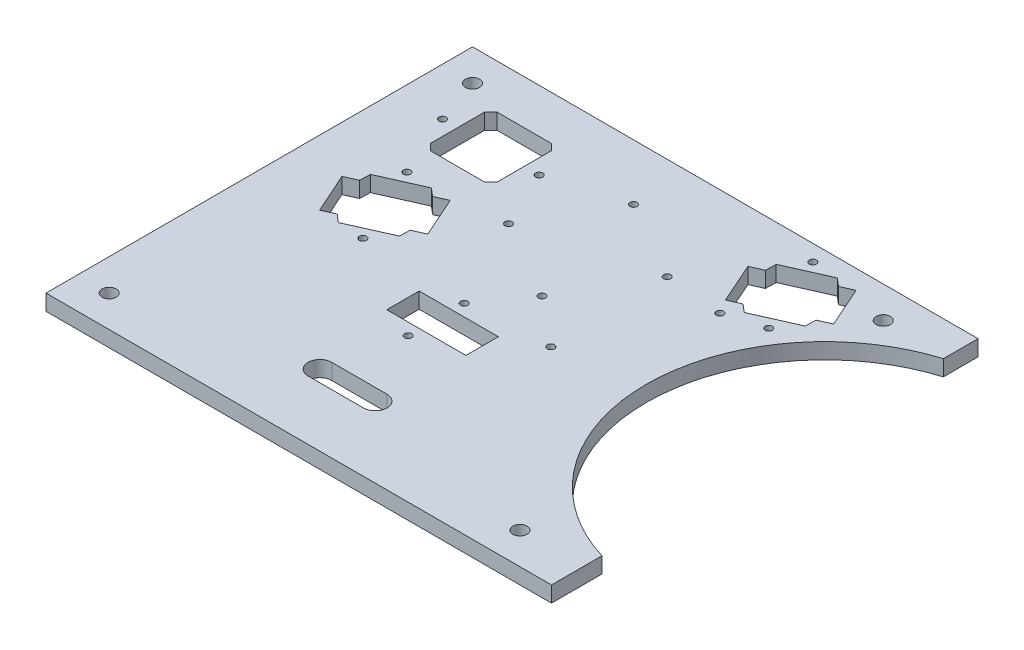
SolidWorks part; units mm, degrees
material "Multistrato di pioppo"
ref_plane "Piano frontale" through (0, 0, 0) normal (0, 0, 1) x (1, 0, 0)
ref_plane "Piano superiore" through (0, 0, 0) normal (0, 1, 0) x (1, 0, 0)
ref_plane "Piano destro" through (0, 0, 0) normal (1, 0, 0) x (0, 0, -1)
sketch "Schizzo1" plane through (0, 0, 0) normal (0, 1, 0) x (1, 0, 0)
  line L1 (-320, 270) -> (0, 270)
  line L2 (-320, 270) -> (-320, 0)
  line L3 (-320, 0) -> (0, 0)
  line L4 (0, 270) -> (0, 0)
  dimension "D1" = 320
  dimension "D2" = 270
extrude "Estrusione-Estrusione1" add sketch "Schizzo1" along normal blind 10
sketch "Schizzo3" plane through (0, 10, 0) normal (0, 1, 0) x (1, 0, 0)
  line L0 (0, 270) -> (-320, 270) construction
  line L1 (-320, 270) -> (-320, 0) construction
  line L2 (-172, 195) -> (-182.6116, 234.603) construction
  line L3 (-172, 195) -> (-172, 236) construction
  line L4 (-172, 195) -> (-161.3884, 155.397) construction
  line L5 (-211.603, 184.3884) -> (-132.397, 205.6116) construction
  circle A5 centre (-132.397, 205.6116) radius 2.25
  circle A6 centre (-161.3884, 155.397) radius 2.25
  circle A7 centre (-182.6116, 234.603) radius 2.25
  circle A8 centre (-211.603, 184.3884) radius 2.25
  circle A9 centre (-172, 195) radius 41 construction
  dimension "D1" = 4.5
  dimension "D2" = 75
  dimension "D3" = 148
  dimension "D5" = 82
  dimension "D4" = 15
extrude "Taglio-Estrusione2" cut sketch "Schizzo3" against normal blind 10
sketch "Schizzo4" plane through (0, 10, 0) normal (0, 1, 0) x (1, 0, 0)
  line L0 (-112.4992, 236.8164) -> (-104.7852, 240.2509)
  line L1 (-65.0971, 257.9212) -> (-53.7084, 232.3419)
  line L2 (-53.7084, 232.3419) -> (-61.4225, 228.9074)
  line L3 (-101.1106, 211.2371) -> (-112.4992, 236.8164)
  line L4 (-242.8894, 178.7629) -> (-231.5008, 153.1836)
  line L5 (-231.5008, 153.1836) -> (-239.2148, 149.7491)
  line L6 (-278.9029, 132.0788) -> (-290.2916, 157.6581)
  line L7 (-290.2916, 157.6581) -> (-282.5775, 161.0926)
  line L8 (-282.5775, 161.0926) -> (-282.4078, 167.736)
  line L9 (-282.4078, 167.736) -> (-255.654, 179.6476)
  line L10 (-255.654, 179.6476) -> (-250.6034, 175.3284)
  line L11 (-239.2148, 149.7491) -> (-239.3845, 143.1058)
  line L12 (-239.3845, 143.1058) -> (-266.1384, 131.1942)
  line L13 (-266.1384, 131.1942) -> (-271.1889, 135.5133)
  line L14 (-104.7852, 240.2509) -> (-104.6155, 246.8942)
  line L15 (-104.6155, 246.8942) -> (-77.8616, 258.8058)
  line L16 (-77.8616, 258.8058) -> (-72.8111, 254.4867)
  line L17 (-93.3966, 214.6716) -> (-88.346, 210.3524)
  line L18 (-88.346, 210.3524) -> (-61.5922, 222.264)
  line L19 (-61.5922, 222.264) -> (-61.4225, 228.9074)
  line L20 (-72.8111, 254.4867) -> (-65.0971, 257.9212)
  line L21 (-93.3966, 214.6716) -> (-101.1106, 211.2371)
  line L22 (-271.1889, 135.5133) -> (-278.9029, 132.0788)
  line L23 (-250.6034, 175.3284) -> (-242.8894, 178.7629)
  circle A0 centre (-272.0814, 180.5434) radius 2.25
  circle A1 centre (-249.7109, 130.2984) radius 2.25
  circle A2 centre (-94.2891, 259.7016) radius 2.25
  circle A3 centre (-71.9186, 209.4566) radius 2.25
  dimension "D1" = 4.5
extrude "Taglio-Estrusione3" cut sketch "Schizzo4" against normal blind 33
hole_wizard "Foro per Vite M8-1" positions "Schizzo5" profile "Schizzo6" hole size "M8" standard "ISO"
sketch "Schizzo5" plane through (0, 10, 0) normal (0, 1, 0) x (1, 0, 0)
  line L1 (-300, 20) -> (-40, 20) construction
  line L2 (-300, 20) -> (-300, 250) construction
  line L3 (-300, 250) -> (-40, 250) construction
  line L4 (-40, 20) -> (-40, 250) construction
  line L5 (-320, 270) -> (-320, 0) construction
  line L6 (-320, 0) -> (0, 0) construction
  line L7 (0, 0) -> (0, 270) construction
  line L8 (0, 270) -> (-320, 270) construction
  point P0 (-300, 20)
  point P2 (-300, 250)
  point P4 (-40, 250)
  point P6 (-40, 20)
  dimension "D1" = 20
  dimension "D2" = 20
  dimension "D3" = 40
  dimension "D4" = 20
sketch "Schizzo6" plane through (-300, 10, -20) normal (1, 0, 0) x (0, 0, 1)
  line L0 (0, 0) -> (0, 190.7039)
  line L1 (0, 190.7039) -> (4.5, 188)
  line L2 (4.5, 188) -> (4.5, 0)
  line L5 (4.5, 0) -> (0, 0)
  line L10 (0, 190.7039) -> (-4.5, 188) construction
  line L11 (0, -6.35) -> (0, 107.95) construction
  dimension "Hole Dia." = 9
  dimension "Hole Depth" = 188
  dimension "Drill Angle" = 118
sketch "Schizzo7" plane through (0, 10, 0) normal (0, 1, 0) x (1, 0, 0)
  line L0 (0, 0) -> (0, 270) construction
  line L1 (0, 270) -> (-320, 270) construction
  circle A0 centre (33, 140) radius 113
  dimension "D1" = 226
  dimension "D2" = 33
  dimension "D3" = 130
extrude "Taglio-Estrusione4" cut sketch "Schizzo7" against normal blind 10
sketch "Schizzo8" plane through (0, 10, 0) normal (0, 1, 0) x (1, 0, 0)
  line L0 (-280.4012, 238) -> (-276.4012, 242)
  line L1 (-276.4012, 242) -> (-242.1012, 242)
  line L2 (-242.1012, 242) -> (-238.1012, 238)
  line L3 (-238.1012, 238) -> (-238.1012, 203.7)
  line L4 (-238.1012, 203.7) -> (-242.1012, 199.7)
  line L5 (-242.1012, 199.7) -> (-276.4012, 199.7)
  line L6 (-276.4012, 199.7) -> (-280.4012, 203.7)
  line L7 (-280.4012, 203.7) -> (-280.4012, 238)
extrude "Taglio-Estrusione5" cut sketch "Schizzo8" against normal blind 22
sketch "Schizzo9" plane through (0, 10, 0) normal (0, 1, 0) x (1, 0, 0)
  circle A0 centre (-228.6012, 220.85) radius 2.25
  circle A1 centre (-289.9012, 220.85) radius 2.25
  dimension "D1" = 4.5
extrude "Taglio-Estrusione6" cut sketch "Schizzo9" against normal blind 42.3
sketch "Schizzo10" plane through (0, 10, 0) normal (0, 1, 0) x (1, 0, 0)
  line L1 (-203, 119.25) -> (-152.9, 119.25)
  line L2 (-203, 119.25) -> (-203, 98.75)
  line L3 (-203, 98.75) -> (-152.9, 98.75)
  line L4 (-152.9, 119.25) -> (-152.9, 98.75)
  line L5 (-162, 98.75) -> (-203, 98.75) construction
  dimension "D1" = 50.1
extrude "Taglio-Estrusione7" cut sketch "Schizzo10" against normal blind 42.3
sketch "Schizzo11" plane through (0, 10, 0) normal (0, 1, 0) x (1, 0, 0)
  circle A0 centre (-182, 91.25) radius 2.25
  circle A1 centre (-182, 126.75) radius 2.25
  dimension "D1" = 4.5
extrude "Taglio-Estrusione8" cut sketch "Schizzo11" against normal blind 18
sketch "Schizzo12" plane through (0, 10, 0) normal (0, 1, 0) x (1, 0, 0)
  circle A0 centre (-95.652, 202.2667) radius 2.25
  circle A1 centre (-130.7217, 130.3632) radius 2.25
  dimension "D1" = 4.5
extrude "Taglio-Estrusione9" cut sketch "Schizzo12" against normal blind 179
sketch "Schizzo13" plane through (0, 10, 0) normal (0, 1, 0) x (1, 0, 0)
  line L0 (-191.5941, 45) -> (-156.5941, 45) construction
  line L1 (-191.5941, 52.5) -> (-156.5941, 52.5)
  line L2 (-191.5941, 37.5) -> (-156.5941, 37.5)
  line L3 (-320, 0) -> (0, 0) construction
  line L4 (-320, 45) -> (-28.1882, 45) construction
  line L5 (-320, 270) -> (-320, 0) construction
  arc A0 (-191.5941, 52.5) -> (-191.5941, 37.5) centre (-191.5941, 45) ccw
  arc A1 (-156.5941, 37.5) -> (-156.5941, 52.5) centre (-156.5941, 45) ccw
  arc A2 (0, 248.074) -> (0, 31.926) centre (33, 140) ccw construction
  point P2 (-174.0941, 45)
  point P17 (-174.0941, 45)
  dimension "D1" = 15
  dimension "D2" = 35
  dimension "D3" = 45
  dimension "D4" = 291.8118
extrude "Taglio-Estrusione10" cut sketch "Schizzo13" against normal blind 179
